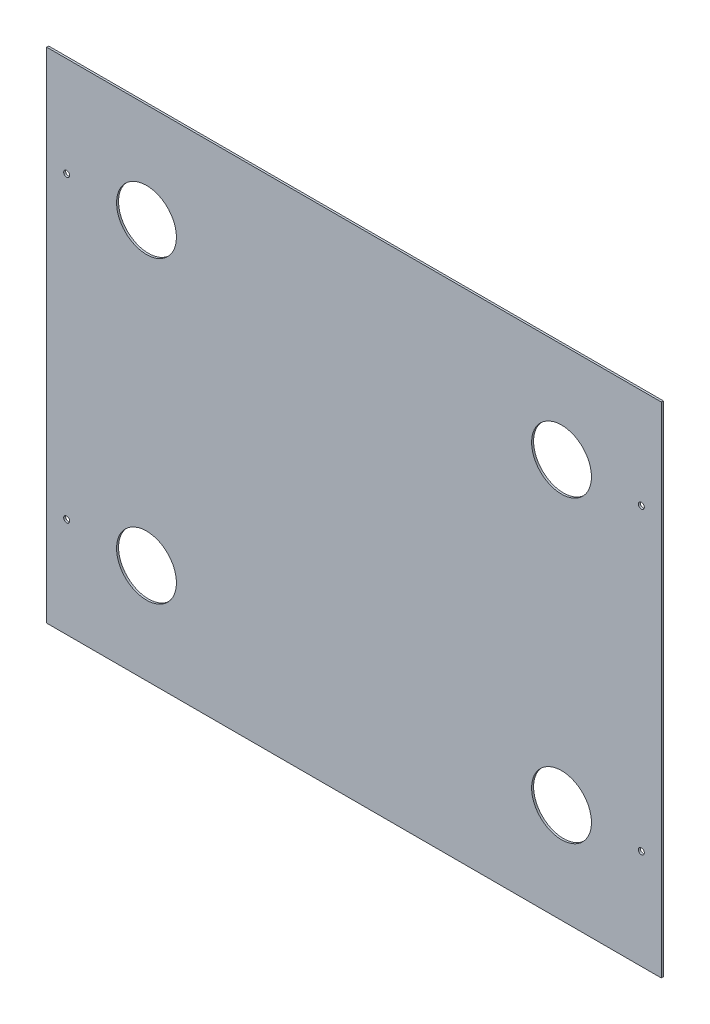
SolidWorks part; units mm, degrees
ref_plane "Plan de face" through (0, 0, 0) normal (0, 0, 1) x (1, 0, 0)
ref_plane "Plan de dessus" through (0, 0, 0) normal (0, 1, 0) x (1, 0, 0)
ref_plane "Plan de droite" through (0, 0, 0) normal (1, 0, 0) x (0, 0, -1)
sketch "Esquisse2" plane through (0, 0, 0) normal (0, 0, 1) x (1, 0, 0)
  line L1 (0, 250) -> (308, 250)
  line L2 (0, 250) -> (0, 0)
  line L3 (0, 0) -> (308, 0)
  line L4 (308, 250) -> (308, 0)
  dimension "D1" = 250
  dimension "D2" = 308
extrude "Boss.-Extru.1" add sketch "Esquisse2" along normal blind 1
sketch "Esquisse3" plane through (0, 0, 1) normal (0, 0, 1) x (1, 0, 0)
  line L0 (0, 250) -> (0, 0) construction
  line L1 (308, 250) -> (0, 250) construction
  line L2 (308, 0) -> (308, 250) construction
  circle A0 centre (10, 200) radius 1.5
  circle A1 centre (298, 200) radius 1.5
  dimension "D1" = 10
  dimension "D3" = 3
  dimension "D4" = 3
  dimension "D2" = 50
  dimension "D5" = 10
extrude "Enlèv. mat.-Extru.1" cut sketch "Esquisse3" against normal through all
pattern_linear "Répétition linéaire1" count 2 spacing 150 along (0, -1, 0) of "Enlèv. mat.-Extru.1"
sketch "Esquisse4" plane through (0, 0, 1) normal (0, 0, 1) x (1, 0, 0)
  line L0 (0, 250) -> (0, 0) construction
  line L1 (308, 250) -> (0, 250) construction
  line L2 (308, 0) -> (308, 250) construction
  line L3 (0, 0) -> (308, 0) construction
  circle A0 centre (50, 200) radius 15
  circle A1 centre (258, 200) radius 15
  circle A2 centre (50, 50) radius 15
  circle A3 centre (258, 50) radius 15
  dimension "D1" = 30
  dimension "D2" = 50
  dimension "D3" = 50
  dimension "D5" = 50
  dimension "D7" = 50
extrude "Enlèv. mat.-Extru.2" cut sketch "Esquisse4" against normal through all
